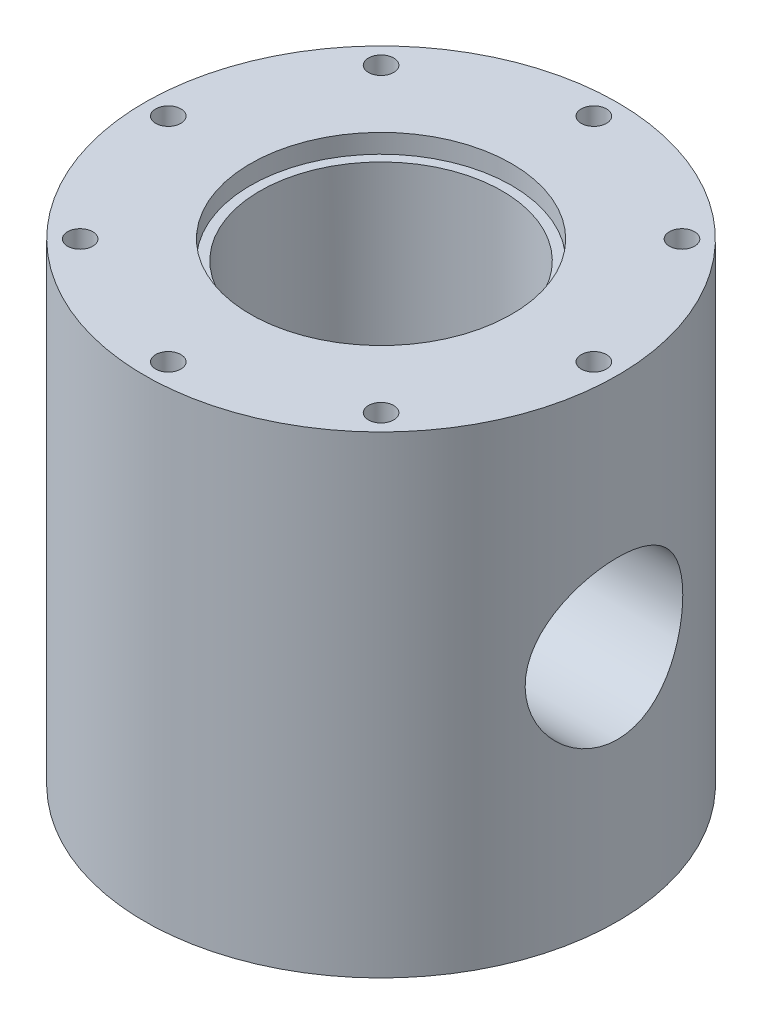
SolidWorks part; units mm, degrees
material "Alumina"
ref_plane "Front Plane" through (0, 0, 0) normal (0, 0, 1) x (1, 0, 0)
ref_plane "Top Plane" through (0, 0, 0) normal (0, 1, 0) x (1, 0, 0)
ref_plane "Right Plane" through (0, 0, 0) normal (1, 0, 0) x (0, 0, -1)
sketch "Sketch1" plane through (0, 0, 0) normal (0, 1, 0) x (1, 0, 0)
  line L0 (-37.5, -37.5) -> (37.5, -37.5)
  line L1 (-37.5, -37.5) -> (-37.5, 37.5)
  line L2 (37.5, -37.5) -> (37.5, 37.5)
  line L3 (-37.5, 37.5) -> (37.5, 37.5)
  line L4 (-37.5, -37.5) -> (37.5, 37.5) construction
  line L5 (37.5, -37.5) -> (-37.5, 37.5) construction
  point P1 (0, 0)
  dimension "D1" = 75
  dimension "D2" = 75
extrude "Boss-Extrude1" add sketch "Sketch1" along normal blind 75
sketch "Sketch2" plane through (0, 0, 0) normal (0, -1, 0) x (-1, 0, 0)
  circle A0 centre (0, 0) radius 5.35
  dimension "D1" = 10.7
extrude "Cut-Extrude1" cut sketch "Sketch2" against normal through all
sketch "Sketch5" plane through (37.5, 0, 0) normal (1, 0, 0) x (0, 0, -1)
  line L0 (0, 0) -> (0, 75) construction
  line L1 (-37.5, 0) -> (37.5, 0) construction
  line L2 (-37.5, 75) -> (37.5, 75) construction
  line L3 (-37.5, 37.5) -> (37.5, 37.5) construction
  line L4 (-37.5, 75) -> (-37.5, 0) construction
  line L5 (37.5, 75) -> (37.5, 0) construction
  circle A0 centre (0, 37.5) radius 12.5
  dimension "D1" = 25
extrude "Cut-Extrude2" cut sketch "Sketch5" against normal through all
sketch "Sketch7" plane through (0, 0, 0) normal (0, -1, 0) x (1, 0, 0)
  circle A0 centre (0, 0) radius 19.21
  circle A1 centre (0, 0) radius 20.71
  dimension "D1" = 38.42
  dimension "D2" = 41.42
extrude "Cut-Extrude3" cut sketch "Sketch7" against normal blind 3
sketch "Sketch8" plane through (0, 0, 0) normal (0, -1, 0) x (1, 0, 0)
  line L4 (-37.5, 37.5) -> (-37.5, -37.5)
  line L5 (-37.5, -37.5) -> (37.5, -37.5)
  line L6 (37.5, -37.5) -> (37.5, 37.5)
  line L7 (37.5, 37.5) -> (-37.5, 37.5)
  line L8 (-37.5, 37.5) -> (-37.5, -37.5)
  line L9 (-37.5, -37.5) -> (37.5, -37.5)
  line L10 (37.5, -37.5) -> (37.5, 37.5)
  line L11 (37.5, 37.5) -> (-37.5, 37.5)
  circle A0 centre (0, 0) radius 20.71 construction
  circle A1 centre (0, 0) radius 20.71
  circle A2 centre (0, 0) radius 30
  dimension "D2" = 37.5
  dimension "D3" = 41.42
  dimension "D4" = 60
  dimension "D1" = 0
sketch "Sketch11" plane through (0, 0, 0) normal (0, -1, 0) x (1, 0, 0)
  line L0 (-37.5, 37.5) -> (-37.5, -37.5) construction
  circle A0 centre (-33.75, 0) radius 2
  circle A1 centre (-23.8649, 23.8649) radius 2
  circle A2 centre (0, 33.75) radius 2
  circle A3 centre (23.8649, 23.8649) radius 2
  circle A4 centre (33.75, 0) radius 2
  circle A5 centre (23.8649, -23.8649) radius 2
  circle A6 centre (0, -33.75) radius 2
  circle A7 centre (-23.8649, -23.8649) radius 2
  point P16 (0, 0)
  dimension "D1" = 4
  dimension "D2" = 3.75
  dimension "D3" = 8
extrude "Cut-Extrude4" cut sketch "Sketch11" against normal blind 10
ref_plane "Plane1" through (0, 37.5, 0) normal (0, 1, 0) x (1, 0, 0)
mirror "Mirror1" about plane through (0, 37.5, 0) normal (0, 1, 0) of "Cut-Extrude3", "Cut-Extrude4"
sketch "Sketch12" plane through (0, 0, 0) normal (0, -1, 0) x (1, 0, 0)
  circle A0 centre (0, 0) radius 37.5
extrude "Cut-Extrude6" cut sketch "Sketch12" against normal through all flip side to cut
sketch "Sketch13" plane through (0, 75, 0) normal (0, 1, 0) x (1, 0, 0)
  circle A0 centre (0, 0) radius 19.21 construction
  circle A1 centre (0, 0) radius 19.21
extrude "Cut-Extrude7" cut sketch "Sketch13" against normal blind 50
sketch "Sketch14" plane through (0, 0, 0) normal (0, -1, 0) x (1, 0, 0)
  circle A0 centre (0, 0) radius 37.5
